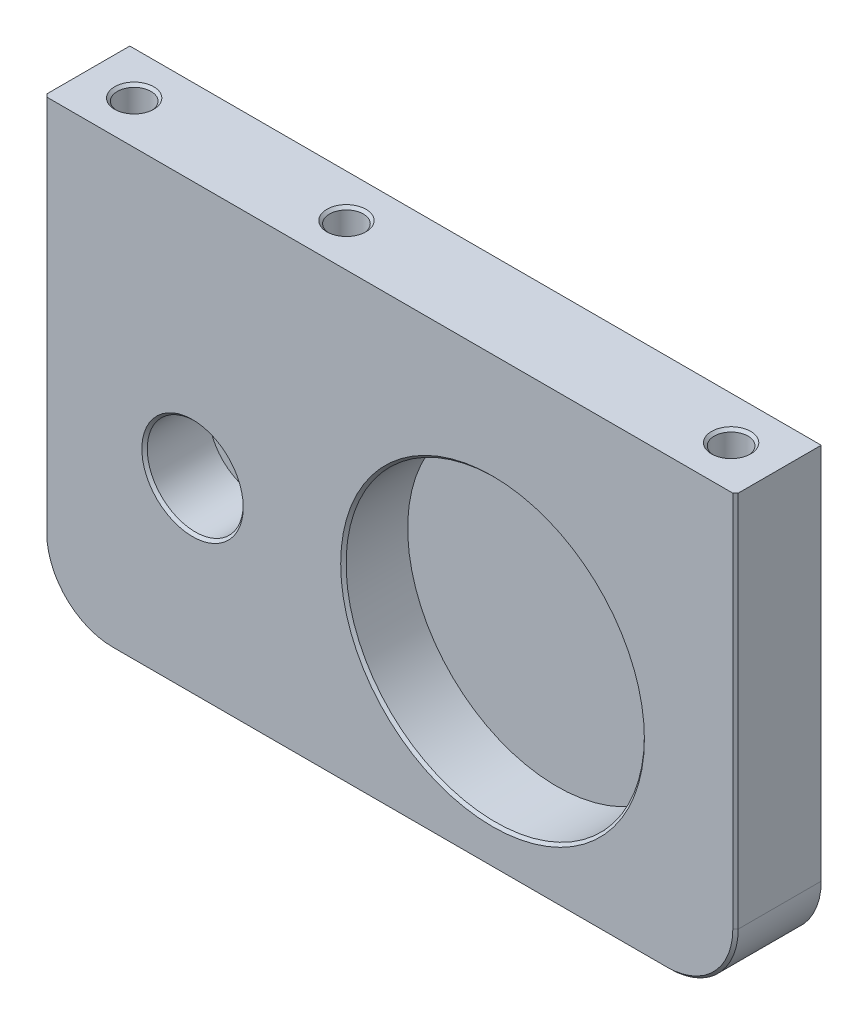
SolidWorks part; units mm, degrees
ref_plane "Front Plane" through (0, 0, 0) normal (0, 0, 1) x (1, 0, 0)
ref_plane "Top Plane" through (0, 0, 0) normal (0, 1, 0) x (1, 0, 0)
ref_plane "Right Plane" through (0, 0, 0) normal (1, 0, 0) x (0, 0, -1)
sketch "Sketch1" plane through (0, 0, 152.1117) normal (0, 0, 1) x (1, 0, 0)
  line L10 (-33.225, 19.05) -> (18, 19.05)
  line L11 (-33.225, 19.05) -> (-33.225, -14)
  line L12 (-33.225, -14) -> (18, -14)
  line L13 (18, 19.05) -> (18, -14)
  circle A2 centre (0, 0) radius 11.05 construction
  circle A3 centre (-22.225, 0) radius 3.556 construction
  dimension "D2" = 7.112
  dimension "D5" = 19.05
  dimension "D6" = 11
  dimension "D3" = 22.225
  dimension "D1" = 22.1
  dimension "D4" = 14
  dimension "D7" = 18
extrude "Boss-Extrude1" add sketch "Sketch1" against normal blind 6.35
sketch "Sketch7" plane through (0, 0, 152.1117) normal (0, 0, 1) x (1, 0, 0)
  circle A0 centre (0, 0) radius 11.05 construction
  circle A1 centre (-22.225, 0) radius 3.556 construction
  circle A2 centre (0, 0) radius 11.05
  circle A3 centre (-22.225, 0) radius 3.556
extrude "Cut-Extrude3" cut sketch "Sketch7" against normal offset from surface (4.7625 mm away) 1.5875 up to face at (-7.6125, 2.525, 145.7617)
sketch "Sketch8" plane through (0, 19.05, 0) normal (0, 1, 0) x (1, 0, 0)
  line L0 (-33.225, -148.9367) -> (18, -148.9367) construction
  line L1 (-33.225, -145.7617) -> (-33.225, -152.1117) construction
  line L2 (18, -145.7617) -> (18, -152.1117) construction
  circle A1 centre (-29.725, -148.9367) radius 1.25
  circle A2 centre (-14, -148.9367) radius 1.25
  circle A3 centre (14.5, -148.9367) radius 1.25
  dimension "D1" = 2.5
  dimension "D2" = 3.5
  dimension "D3" = 3.5
  dimension "D4" = 14
extrude "Cut-Extrude4" cut sketch "Sketch8" against normal blind 15
fillet "Fillet3" radius 5.08 2 edges at (18, -14, 148.9367) (-33.225, -14, 148.9367)
chamfer "Chamfer2" distance 0.2 angle 45 10 edges at (-18.669, 0, 152.1117) (14.5, 19.05, 150.1867) (-29.725, 19.05, 150.1867) (-14, 19.05, 150.1867) (11.05, 0, 152.1117) (18, 5.065, 152.1117) (-33.225, 5.065, 152.1117) (-7.6125, -14, 152.1117) (16.5121, -12.5121, 152.1117) (-31.7371, -12.5121, 152.1117)
